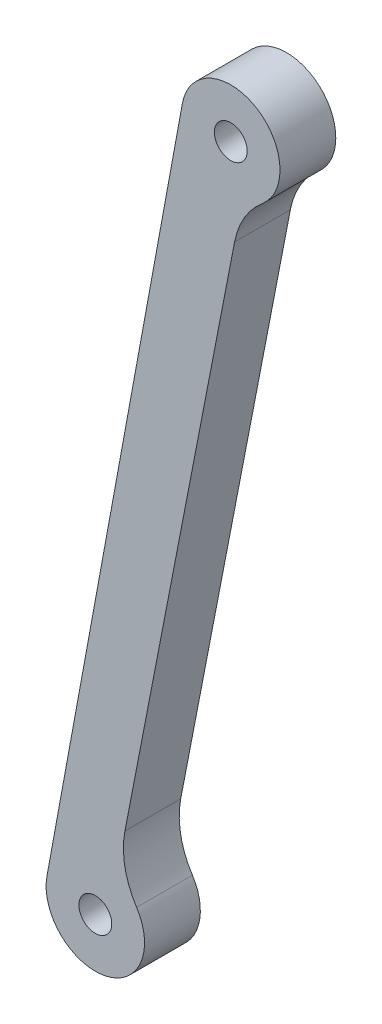
SolidWorks part; units mm, degrees
ref_plane "Спереди" through (0, 0, 0) normal (0, 0, 1) x (1, 0, 0)
ref_plane "Сверху" through (0, 0, 0) normal (0, 1, 0) x (1, 0, 0)
ref_plane "Справа" through (0, 0, 0) normal (1, 0, 0) x (0, 0, -1)
sketch "Sketch5" plane through (0, 0, 0) normal (0, 0, 1) x (1, 0, 0)
  line L0 (1.7523, 0.4742) -> (37.3029, 86.8114) construction
  line L1 (-1.0106, -0.6044) -> (29.6618, 87.5839) construction
  line L2 (0, 0) -> (17.8901, 43.1295)
  line L3 (0, 0) -> (114.3643, 0) construction
  line L4 (23.8823, 39.6684) -> (24.5035, 51.2503)
  line B0 (17.4507, 115.16) -> (29.9551, 112.6983)
  spline B1 degree 3 poles (29.9551, 112.6983) (28.321, 116.0983) (27.9284, 121.1676) (30.1713, 134.4746) (29.8473, 132.0116) (30.6222, 139.9349) (27.0176, 140.9027) knots 0 0 0 0 0.297085 0.369784 0.687298 1 1 1 1
  spline B2 degree 2 poles (27.0176, 140.9027) (20.5603, 128.6427) (17.4507, 115.16) knots 0 0 0 1 1 1
  spline B3 degree 2 poles (27.0176, 140.9027) (26.5004, 134.6878) (22.2537, 130.5645) knots 0 0 0 1 1 1
  line B4 (17.1977, 114.3508) -> (29.842, 112.2111)
  line B5 (28.7001, 84.8969) -> (10.3668, 87.513)
  spline B6 degree 1 poles (17.1977, 114.3508) (10.3668, 87.513) knots 0 0 1 1
  spline B7 degree 2 poles (29.842, 112.2111) (22.5534, 98.8452) (28.7001, 84.8969) knots 0 0 0 1 1 1
  line B8 (10.1904, 87.4159) -> (28.2572, 84.4958)
  line B9 (32.8909, 45.7292) -> (10.0695, 42.8593)
  spline B10 degree 2 poles (10.1904, 87.4159) (10.0234, 65.1379) (10.0695, 42.8593) knots 0 0 0 1 1 1
  spline B11 degree 2 poles (28.2572, 84.4958) (20.6417, 64.1094) (32.8909, 45.7292) knots 0 0 0 1 1 1
  line B12 (10.2797, 36.8758) -> (3.9253, -13.9853)
  line B13 (3.9253, -13.9853) -> (33.9594, -31.0804)
  line B14 (33.9594, -31.0804) -> (45.9193, -27.7969)
  line B15 (45.9193, -27.7969) -> (58.2918, -13.9853)
  line B16 (58.2918, -13.9853) -> (69.0331, -4.9875)
  line B17 (69.0331, -4.9875) -> (82.514, 2.0236)
  line B18 (82.514, 2.0236) -> (89.2736, 3.8794)
  line B19 (89.2736, 3.8794) -> (92.4846, 9.5208)
  line B20 (92.4846, 9.5208) -> (96.8914, 17.263)
  line B21 (96.8914, 17.263) -> (101.4978, 21.1217)
  line B22 (101.4978, 21.1217) -> (103.9241, 23.1541)
  line B23 (104.261, 27.4157) -> (104.5375, 25.5318)
  line B24 (84.192, 21.2056) -> (87.7484, 22.7822)
  line B25 (87.7484, 22.7822) -> (92.912, 27.4956)
  line B26 (71.6086, 15.6268) -> (84.192, 21.2056)
  line B27 (92.912, 27.4956) -> (95.357, 29.7274)
  line B28 (95.357, 29.7274) -> (96.8049, 29.9399)
  line B29 (71.6086, 15.6268) -> (53.4239, 15.2713)
  line B30 (48.0904, 17.5622) -> (39.9394, 26.4919)
  line B31 (39.9394, 26.4919) -> (33.9594, 37.99)
  line B32 (33.9594, 37.99) -> (10.2797, 36.8758)
  line B33 (96.8049, 29.9399) -> (99.4078, 30.2175)
  line B34 (99.4078, 30.2175) -> (102.2786, 29.261)
  line B35 (102.2786, 29.261) -> (104.261, 27.4157)
  line B36 (104.5375, 25.5318) -> (103.9241, 23.1541)
  arc B37 (53.4239, 15.2713) -> (48.0904, 17.5622) centre (53.2864, 22.3051) cw
  spline B38 degree 3 poles (104.261, 27.4157) (103.5289, 27.0494) (99.8378, 26.2685) (94.8982, 17.2338) (98.6516, 18.7375) knots 0 0 0 0 0.441207 1 1 1 1
  line B39 (27.7375, 116.5129) -> (14.1959, 87.8955)
  line B40 (27.7375, 116.5129) -> (25.9485, 114.8372)
  line B41 (25.9485, 114.8372) -> (27.5763, 114.067)
  line B42 (27.7375, 116.5129) -> (27.5763, 114.067)
  line B43 (26.1527, 88.0864) -> (17.8901, 43.1295)
  line B44 (19.3622, 85.005) -> (23.8823, 39.6684)
  line B45 (19.3622, 85.005) -> (17.7584, 73.9508)
  line B46 (17.7584, 73.9508) -> (23.117, 74.485)
  line B47 (23.117, 74.485) -> (19.3622, 85.005)
  line B48 (26.1527, 88.0864) -> (23.7481, 82.7635)
  line B49 (23.7481, 82.7635) -> (25.1278, 82.5099)
  line B50 (25.1278, 82.5099) -> (26.5087, 82.2561)
  line B51 (26.5087, 82.2561) -> (26.1527, 88.0864)
  line B52 (26.1527, 88.0864) -> (19.3622, 85.005)
  line B53 (19.3622, 85.005) -> (22.3683, 87.7853)
  line B54 (22.3683, 87.7853) -> (22.9012, 86.6109)
  line B55 (22.9012, 86.6109) -> (23.4998, 85.2917)
  line B56 (23.4998, 85.2917) -> (19.3622, 85.005)
  dimension "D1" = 93.37
  dimension "D2" = 93.37
  dimension "D4" = 67.471
  dimension "D5" = 8.764
sketch_block_instance "Block1-1"
sketch_block "Block1"
sketch_block_instance "Block2-1"
sketch_block "Block2"
sketch_block_instance "Block3-1"
sketch_block "Block3"
sketch_block_instance "Block18-1"
sketch_block "Block18"
sketch_block_instance "Block44-1"
sketch_block "Block44"
sketch_block_instance "Block46-1"
sketch_block "Block46"
sketch_block_instance "Block47-1"
sketch_block "Block47"
sketch_block_instance "Block48-1"
sketch_block "Block48"
sketch_block_instance "Block50-1"
sketch_block "Block50"
sketch "Sketch7" plane through (0, 0, 0) normal (0, 0, 1) x (1, 0, 0)
  line L0 (14.9395, 43.6718) -> (23.1953, 88.5924)
  line L1 (19.6932, 48.436) -> (26.3767, 82.8719)
  arc A0 (14.9395, 43.6718) -> (20.4069, 44.7622) centre (17.8901, 43.1295) ccw
  arc A1 (28.0731, 85.7511) -> (23.1953, 88.5924) centre (26.1459, 88.0502) ccw
  circle A2 centre (17.8901, 43.1295) radius 1
  circle A3 centre (26.1459, 88.0502) radius 1
  arc A4 (26.3767, 82.8719) -> (28.0731, 85.7511) centre (31.2851, 81.9192) cw
  arc A5 (19.6932, 48.436) -> (20.4069, 44.7622) centre (24.6016, 47.4833) ccw
  dimension "D1" = 2
  dimension "D2" = 6
  dimension "D3" = 5
extrude "Boss-Extrude2" add sketch "Sketch7" along normal blind 3.4
